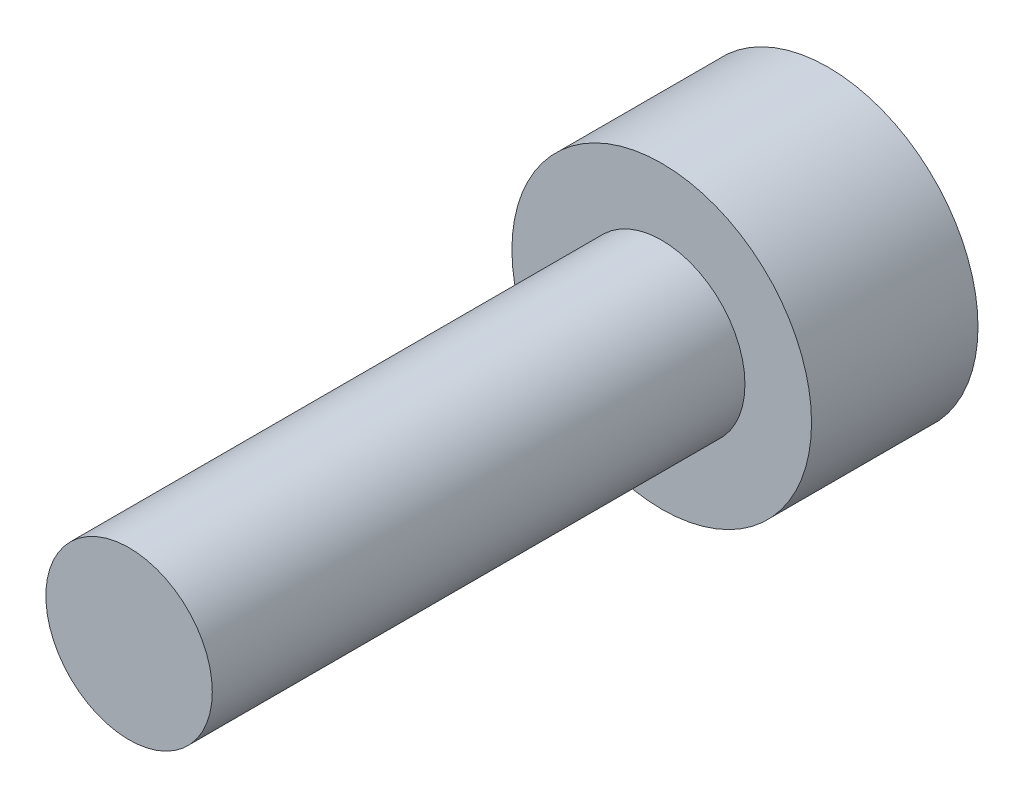
SolidWorks part; units mm, degrees
material "Acero aleado"
ref_plane "Alzado" through (0, 0, 0) normal (0, 0, 1) x (1, 0, 0)
ref_plane "Planta" through (0, 0, 0) normal (0, 1, 0) x (1, 0, 0)
ref_plane "Vista lateral" through (0, 0, 0) normal (1, 0, 0) x (0, 0, -1)
sketch "Croquis1" plane through (0, 0, 0) normal (0, 0, 1) x (1, 0, 0)
  circle A0 centre (0, 0) radius 2.25
  dimension "D1" = 4.5
extrude "Cabeza" add sketch "Croquis1" along normal blind 2.5 from offset 2.5
sketch "Croquis2" plane through (0, 0, 0) normal (0, 0, 1) x (1, 0, 0)
  circle A0 centre (0, 0) radius 1.25
  dimension "D1" = 2.5
extrude "Cuerpo" add sketch "Croquis2" along normal blind 8
sketch "Croquis3" plane through (0, 0, 0) normal (0, 0, 1) x (1, 0, 0)
  line L0 (1.1547, 0) -> (0.5774, 1)
  line L1 (0.5774, 1) -> (-0.5774, 1)
  line L2 (-0.5774, 1) -> (-1.1547, 0)
  line L3 (-1.1547, 0) -> (-0.5774, -1)
  line L4 (-0.5774, -1) -> (0.5774, -1)
  line L5 (0.5774, -1) -> (1.1547, 0)
  dimension "D1" = 1.1547
  dimension "D2" = 0.5774
  dimension "D3" = 1
  dimension "D4" = 0.5774
  dimension "D5" = 1
  dimension "D6" = 1.1547
  dimension "D7" = 0.5774
  dimension "D8" = 1
  dimension "D9" = 0.5774
  dimension "D10" = 1
extrude "Hexagono_interior" cut sketch "Croquis3" along normal blind 1.1 from offset 2.5
